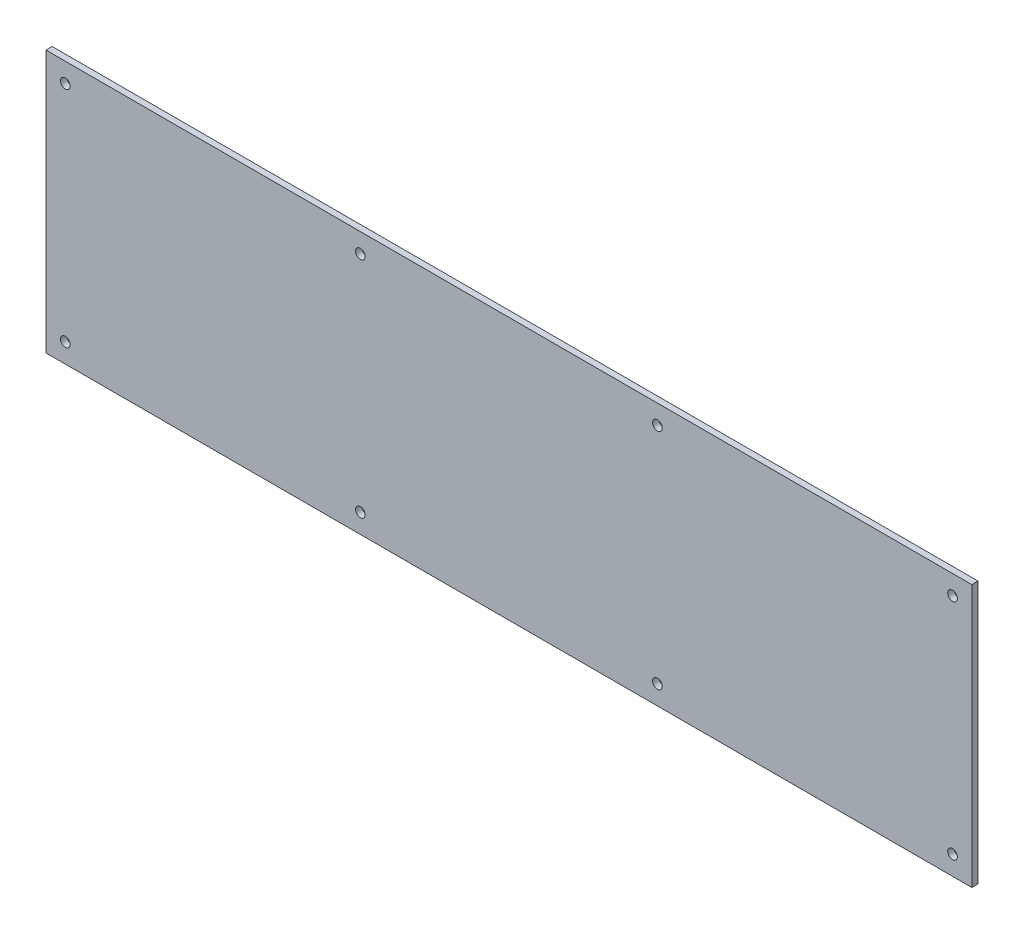
SolidWorks part; units mm, degrees
material "Acrylic (Medium-high impact)"
ref_plane "Front Plane" through (0, 0, 0) normal (0, 0, 1) x (1, 0, 0)
ref_plane "Top Plane" through (0, 0, 0) normal (0, 1, 0) x (1, 0, 0)
ref_plane "Right Plane" through (0, 0, 0) normal (1, 0, 0) x (0, 0, -1)
sketch "Sketch1" plane through (0, 0, 0) normal (0, 0, 1) x (1, 0, 0)
  line L1 (0, 228.6) -> (304.8, 228.6)
  line L2 (0, 228.6) -> (0, 142.24)
  line L3 (0, 142.24) -> (304.8, 142.24)
  line L4 (304.8, 228.6) -> (304.8, 142.24)
extrude "Extrude1" add sketch "Sketch1" along normal blind 2.032
sketch "Sketch2" plane through (0, 0, 2.032) normal (0, 0, 1) x (1, 0, 0)
  line L0 (6.35, 116.84) -> (6.35, 242.7912) construction
  line L1 (103.505, 116.84) -> (103.505, 261.7694) construction
  line L4 (0, 148.59) -> (304.8, 148.59)
  line L5 (0, 148.59) -> (279.4, 148.59) construction
  line L6 (152.4, 142.24) -> (152.4, 299.1279) construction
  line L7 (304.8, 222.25) -> (0, 222.25)
  line L8 (304.8, 222.25) -> (25.4, 222.25) construction
  circle A0 centre (6.35, 222.25) radius 1.5875
  circle A1 centre (6.35, 148.59) radius 1.5875
  circle A2 centre (103.505, 222.25) radius 1.5875
  circle A3 centre (103.505, 148.59) radius 1.5875
  circle A4 centre (201.295, 148.59) radius 1.5875
  circle A5 centre (201.295, 222.25) radius 1.5875
  circle A6 centre (298.45, 148.59) radius 1.5875
  circle A7 centre (298.45, 222.25) radius 1.5875
  dimension "D3" = 3.175
  dimension "D1" = 6.35
  dimension "D2" = 6.35
extrude "Cut-Extrude1" cut sketch "Sketch2" against normal through all
